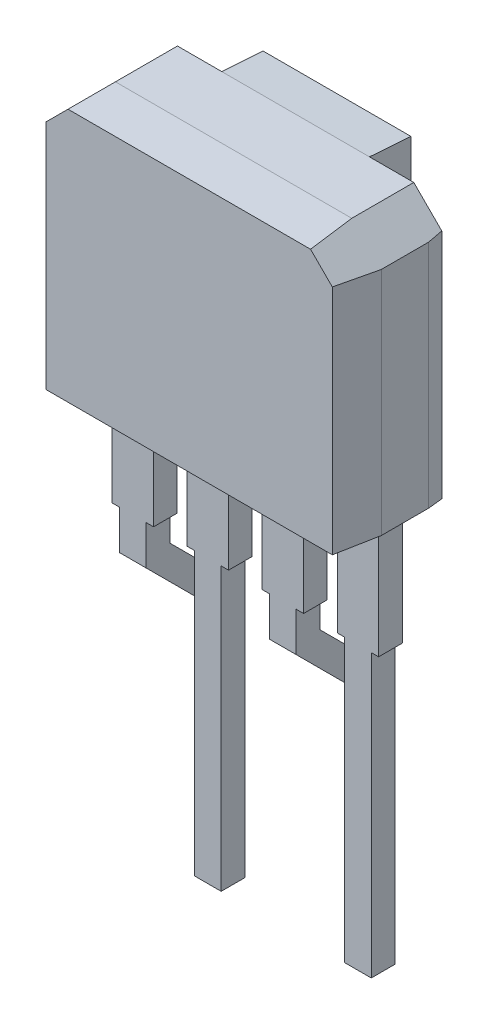
SolidWorks part; units mm, degrees
ref_plane "Front Plane" through (0, 0, 0) normal (0, 0, 1) x (1, 0, 0)
ref_plane "Top Plane" through (0, 0, 0) normal (0, 1, 0) x (1, 0, 0)
ref_plane "Right Plane" through (0, 0, 0) normal (1, 0, 0) x (0, 0, -1)
sketch "Sketch1" plane through (0, 0, 0) normal (0, 1, 0) x (1, 0, 0)
  line L0 (-2.5, 0) -> (-2.5, 1.8)
  line L1 (-2.5, 1.8) -> (-1.25, 1.8)
  line L2 (-1.25, 1.8) -> (-1.25, 2.5)
  line L3 (-1.25, 2.5) -> (1.25, 2.5)
  line L4 (1.25, 2.5) -> (1.25, 1.8)
  line L5 (1.25, 1.8) -> (2.5, 1.8)
  line L6 (2.5, 1.8) -> (2.5, 0)
  line L7 (2.5, 0) -> (-2.5, 0)
  dimension "D1" = 2.5
  dimension "D2" = 5
  dimension "D3" = 2.5
  dimension "D4" = 1.8
extrude "Boss-Extrude1" add sketch "Sketch1" along normal blind 4.4
chamfer "Chamfer5" distance 0.5 distance2 0.5 2 edges at (2.5, 4.4, -0.9) (-2.5, 4.4, -0.9)
chamfer "Chamfer1" distance 0.25 angle 6 2 edges at (-2.5, 1.95, -1.8) (2.5, 1.95, -1.8)
chamfer "Chamfer2" distance 0.75 angle 6 2 edges at (2.5, 1.95, 0) (-2.5, 1.95, 0)
chamfer "Chamfer3" distance 0.75 angle 4 2 edges at (0, 4.4, 0) (0, 0, 0)
chamfer "Chamfer4" distance 0.7 angle 4 2 edges at (0, 0, -2.5) (0, 4.4, -2.5)
sketch "Sketch4" plane through (0, 0, 0) normal (1, 0, 0) x (0, 0, -1)
  line L0 (0.95, 0) -> (0.95, -2.6657)
  line L1 (0.75, 0) -> (1.55, 0) construction
  line L2 (0.95, -2.6657) -> (2.22, -3.9357)
  line L3 (2.22, -3.9357) -> (2.22, -6.77)
  line L4 (2.22, -6.77) -> (2.62, -6.77)
  line L5 (2.62, -6.77) -> (2.62, -3.77)
  line L6 (2.62, -3.77) -> (1.35, -2.5)
  line L7 (1.35, -2.5) -> (1.35, 0)
  line L8 (1.35, 0) -> (0.95, 0)
  line L9 (0, 0.0524) -> (0, 3.9788) construction
  dimension "D1" = 0.4
  dimension "D2" = 0.4
  dimension "D3" = 0.95
  dimension "D4" = 2.5
  dimension "D5" = 1.27
  dimension "D6" = 3
  dimension "D7" = 1.27
extrude "Boss-Extrude2" add sketch "Sketch4" along normal blind 0.45 from offset 0.41
sketch "Sketch5" plane through (0, 0, 0) normal (1, 0, 0) x (0, 0, -1)
  line L0 (0.95, 0) -> (0.95, -6.77)
  line L1 (0.95, -6.77) -> (1.35, -6.77)
  line L2 (1.35, -6.77) -> (1.35, 0)
  line L3 (1.35, 0) -> (0.95, 0)
  line L4 (2.22, -6.77) -> (2.62, -6.77) construction
extrude "Boss-Extrude3" add sketch "Sketch5" along normal blind 0.45 from offset 1.68
pattern_linear "LPattern1" count 2 spacing 2.54 along (-1, 0, 0) of "Boss-Extrude3", "Boss-Extrude2"
sketch "Sketch6" plane through (0, 0, -1.35) normal (0, 0, -1) x (-1, 0, 0)
  line L1 (-2.13, 0) -> (-2.255, 0)
  line L2 (-2.13, 0) -> (-2.13, -2)
  line L3 (-2.13, -2) -> (-2.255, -2)
  line L4 (-2.255, 0) -> (-2.255, -2)
  line L5 (-1.68, 0) -> (-1.555, 0)
  line L6 (-1.68, 0) -> (-1.68, -2)
  line L7 (-1.68, -2) -> (-1.555, -2)
  line L8 (-1.555, 0) -> (-1.555, -2)
  dimension "D1" = 2
  dimension "D2" = 0.7
extrude "Boss-Extrude4" add sketch "Sketch6" against normal up to surface (0.4 mm away) up to face at (1.905, -3.385, -0.95)
pattern_linear "LPattern2" count 4 spacing 1.27 along (-1, 0, 0) of "Boss-Extrude4"
